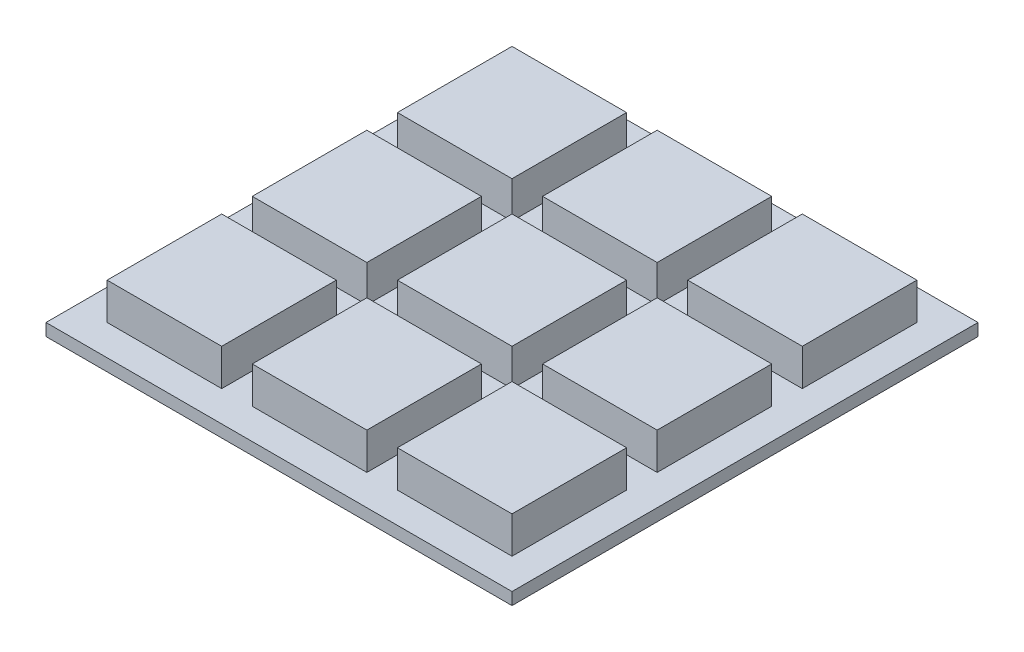
SolidWorks part; units mm, degrees
ref_plane "Front Plane" through (0, 0, 0) normal (0, 0, 1) x (1, 0, 0)
ref_plane "Top Plane" through (0, 0, 0) normal (0, 1, 0) x (1, 0, 0)
ref_plane "Right Plane" through (0, 0, 0) normal (1, 0, 0) x (0, 0, -1)
sketch "Sketch1" plane through (0, 0, 0) normal (0, 1, 0) x (1, 0, 0)
  line L1 (30.5, -30.5) -> (-30.5, -30.5)
  line L2 (30.5, -30.5) -> (30.5, 30.5)
  line L3 (30.5, 30.5) -> (-30.5, 30.5)
  line L4 (-30.5, -30.5) -> (-30.5, 30.5)
  line L5 (30.5, -30.5) -> (-30.5, 30.5) construction
  line L6 (30.5, 30.5) -> (-30.5, -30.5) construction
  point P0 (0, 0)
  dimension "D1" = 61
  dimension "D2" = 61
extrude "Boss-Extrude1" add sketch "Sketch1" along normal blind 1.6
sketch "Sketch2" plane through (0, 1.6, 0) normal (0, 1, 0) x (1, 0, 0)
  line L1 (-26.5, 26.5) -> (-11.5, 26.5)
  line L2 (-26.5, 26.5) -> (-26.5, 11.5)
  line L3 (-26.5, 11.5) -> (-11.5, 11.5)
  line L4 (-11.5, 26.5) -> (-11.5, 11.5)
  line L5 (-26.5, 26.5) -> (-11.5, 11.5) construction
  line L6 (-26.5, 11.5) -> (-11.5, 26.5) construction
  line L7 (-7.5, 26.5) -> (7.5, 26.5)
  line L8 (-7.5, 26.5) -> (-7.5, 11.5)
  line L9 (-7.5, 11.5) -> (7.5, 11.5)
  line L10 (7.5, 26.5) -> (7.5, 11.5)
  line L11 (-7.5, 26.5) -> (7.5, 11.5) construction
  line L12 (-7.5, 11.5) -> (7.5, 26.5) construction
  line L13 (11.5, 26.5) -> (26.5, 26.5)
  line L14 (11.5, 26.5) -> (11.5, 11.5)
  line L15 (11.5, 11.5) -> (26.5, 11.5)
  line L16 (26.5, 26.5) -> (26.5, 11.5)
  line L17 (11.5, 26.5) -> (26.5, 11.5) construction
  line L18 (11.5, 11.5) -> (26.5, 26.5) construction
  line L19 (11.5, 7.5) -> (26.5, 7.5)
  line L20 (11.5, 7.5) -> (11.5, -7.5)
  line L21 (11.5, -7.5) -> (26.5, -7.5)
  line L22 (26.5, 7.5) -> (26.5, -7.5)
  line L23 (11.5, 7.5) -> (26.5, -7.5) construction
  line L24 (11.5, -7.5) -> (26.5, 7.5) construction
  line L25 (-7.5, 7.5) -> (7.5, 7.5)
  line L26 (-7.5, 7.5) -> (-7.5, -7.5)
  line L27 (-7.5, -7.5) -> (7.5, -7.5)
  line L28 (7.5, 7.5) -> (7.5, -7.5)
  line L29 (-7.5, 7.5) -> (7.5, -7.5) construction
  line L30 (-7.5, -7.5) -> (7.5, 7.5) construction
  line L31 (-26.5, 7.5) -> (-11.5, 7.5)
  line L32 (-26.5, 7.5) -> (-26.5, -7.5)
  line L33 (-26.5, -7.5) -> (-11.5, -7.5)
  line L34 (-11.5, 7.5) -> (-11.5, -7.5)
  line L35 (-26.5, 7.5) -> (-11.5, -7.5) construction
  line L36 (-26.5, -7.5) -> (-11.5, 7.5) construction
  line L37 (-26.5, -11.5) -> (-11.5, -11.5)
  line L38 (-26.5, -11.5) -> (-26.5, -26.5)
  line L39 (-26.5, -26.5) -> (-11.5, -26.5)
  line L40 (-11.5, -11.5) -> (-11.5, -26.5)
  line L41 (-26.5, -11.5) -> (-11.5, -26.5) construction
  line L42 (-26.5, -26.5) -> (-11.5, -11.5) construction
  line L43 (-7.5, -11.5) -> (7.5, -11.5)
  line L44 (-7.5, -11.5) -> (-7.5, -26.5)
  line L45 (-7.5, -26.5) -> (7.5, -26.5)
  line L46 (7.5, -11.5) -> (7.5, -26.5)
  line L47 (-7.5, -11.5) -> (7.5, -26.5) construction
  line L48 (-7.5, -26.5) -> (7.5, -11.5) construction
  line L49 (11.5, -11.5) -> (26.5, -11.5)
  line L50 (11.5, -11.5) -> (11.5, -26.5)
  line L51 (11.5, -26.5) -> (26.5, -26.5)
  line L52 (26.5, -11.5) -> (26.5, -26.5)
  line L53 (11.5, -11.5) -> (26.5, -26.5) construction
  line L54 (11.5, -26.5) -> (26.5, -11.5) construction
  point P0 (-19, 19)
  point P5 (0, 19)
  point P10 (19, 19)
  point P15 (19, 0)
  point P20 (0, 0)
  point P25 (-19, 0)
  point P30 (-19, -19)
  point P35 (0, -19)
  point P40 (19, -19)
  point P45 (-19.648, -19.4772)
  point P46 (0, 0)
  dimension "D1" = 15
  dimension "D2" = 4
  dimension "D3" = 4
  dimension "D4" = 4
  dimension "D5" = 4
extrude "Boss-Extrude2" add sketch "Sketch2" along normal blind 4.8
